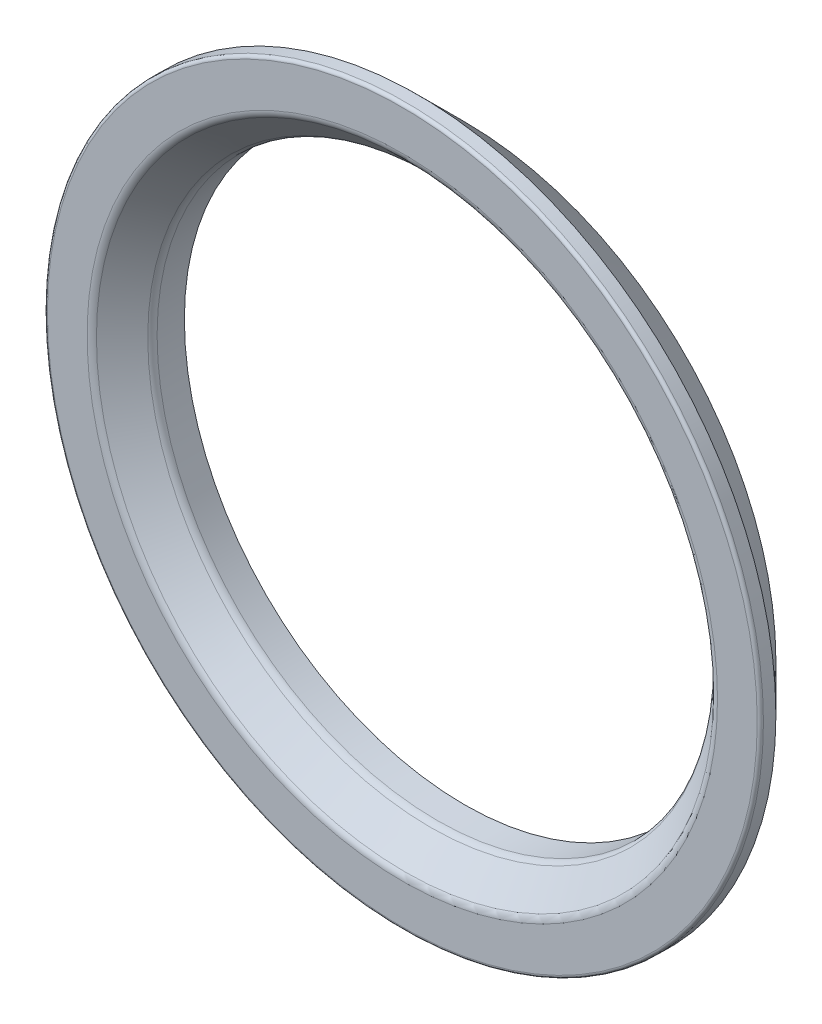
SolidWorks part; units mm, degrees
material "moto_grey"
ref_plane "Front Plane" through (0, 0, 0) normal (0, 0, 1) x (1, 0, 0)
ref_plane "Top Plane" through (0, 0, 0) normal (0, 1, 0) x (1, 0, 0)
ref_plane "Right Plane" through (0, 0, 0) normal (1, 0, 0) x (0, 0, -1)
sketch "Sketch1" plane through (0, 0, 0) normal (0, 0, 1) x (1, 0, 0)
  circle A0 centre (0, 0) radius 11.5
  dimension "D1" = 23
extrude "Boss-Extrude1" add sketch "Sketch1" along normal blind 2
chamfer "Chamfer1" distance 1.5 angle 45 1 edges at (11.5, 0, 0)
sketch "Sketch3" plane through (0, 0, 2) normal (0, 0, 1) x (1, 0, 0)
  circle A0 centre (0, 0) radius 9
  dimension "D1" = 18
extrude "Cut-Extrude1" cut sketch "Sketch3" against normal blind 2
chamfer "Chamfer2" distance 1 angle 45 1 edges at (9, 0, 2)
fillet "Fillet1" radius 0.3 2 edges at (10, 0, 2) (9, 0, 1)
fillet "Fillet2" radius 0.1 1 edges at (11.5, 0, 2)
